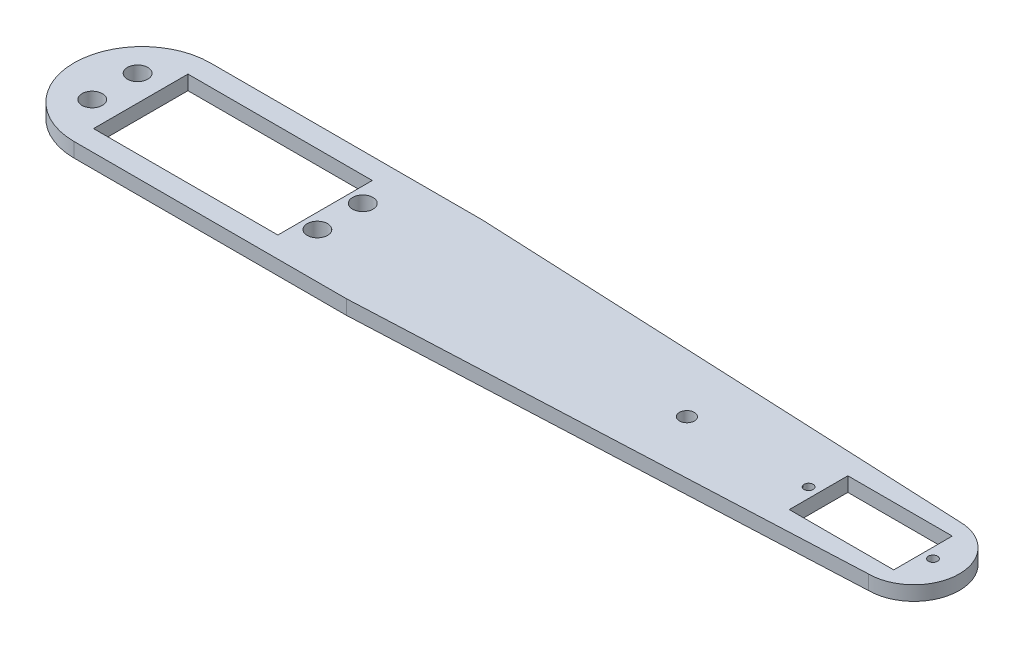
SolidWorks part; units mm, degrees
ref_plane "Front Plane" through (0, 0, 0) normal (0, 0, 1) x (1, 0, 0)
ref_plane "Top Plane" through (0, 0, 0) normal (0, 1, 0) x (1, 0, 0)
ref_plane "Right Plane" through (0, 0, 0) normal (1, 0, 0) x (0, 0, -1)
sketch "Sketch1" plane through (0, 0, 0) normal (0, 1, 0) x (1, 0, 0)
  line L0 (-162.3874, 17.2447) -> (-102.3874, 17.2447)
  line L1 (-102.3874, 17.2447) -> (7.6126, 12.2447)
  line L2 (-162.3874, -12.7553) -> (-102.3874, -12.7553)
  line L3 (-102.3874, -12.7553) -> (7.6126, -7.7553)
  line L4 (-168.3874, 19.311) -> (-168.3874, -13.0468) construction
  line L5 (-15.5874, 2.2447) -> (11.8126, 2.2447) construction
  line L6 (-162.6926, -8.1553) -> (-122.0926, -8.1553)
  line L7 (-162.6926, -8.1553) -> (-162.6926, 12.6447)
  line L8 (-162.6926, 12.6447) -> (-122.0926, 12.6447)
  line L9 (-122.0926, -8.1553) -> (-122.0926, 12.6447)
  line L10 (-13.3874, 8.6947) -> (9.6126, 8.6947)
  line L11 (-13.3874, 8.6947) -> (-13.3874, -4.2053)
  line L12 (-13.3874, -4.2053) -> (9.6126, -4.2053)
  line L13 (9.6126, 8.6947) -> (9.6126, -4.2053)
  line L14 (-13.3874, 8.6947) -> (9.6126, -4.2053) construction
  line L15 (-13.3874, -4.2053) -> (9.6126, 8.6947) construction
  arc A0 (-162.3874, 17.2447) -> (-162.3874, -12.7553) centre (-162.3874, 2.2447) ccw
  arc A1 (7.6126, -7.7553) -> (7.6126, 12.2447) centre (7.6126, 2.2447) ccw
  circle A3 centre (-168.3874, 7.2447) radius 2.25
  circle A4 centre (-168.3874, -2.7553) radius 2.25
  circle A5 centre (-118.7874, 7.2447) radius 2.25
  circle A6 centre (-118.7874, -2.7553) radius 2.25
  circle A7 centre (-15.5874, 2.2447) radius 1
  circle A8 centre (11.8126, 2.2447) radius 1
  circle A9 centre (-42.3874, 2.2447) radius 1.65
  point P20 (-1.8874, 2.2447)
  dimension "D6" = 4.5
  dimension "D17" = 2
  dimension "D18" = 3.3
  dimension "D2" = 30
  dimension "D3" = 20
  dimension "D4" = 5
  dimension "D5" = 5
  dimension "D7" = 49.6
  dimension "D8" = 60
  dimension "D9" = 170
  dimension "D10" = 6
  dimension "D11" = 0
  dimension "D12" = 20.8
  dimension "D13" = 40.6
  dimension "D14" = 12.9
  dimension "D15" = 23
  dimension "D16" = 27.4
  dimension "D19" = 0.3053
  dimension "D20" = 2
  dimension "D21" = 50
extrude "Boss-Extrude1" add sketch "Sketch1" along normal blind 3.175
equation "\"D5@Sketch1\"=\"D4@Sketch1\""
